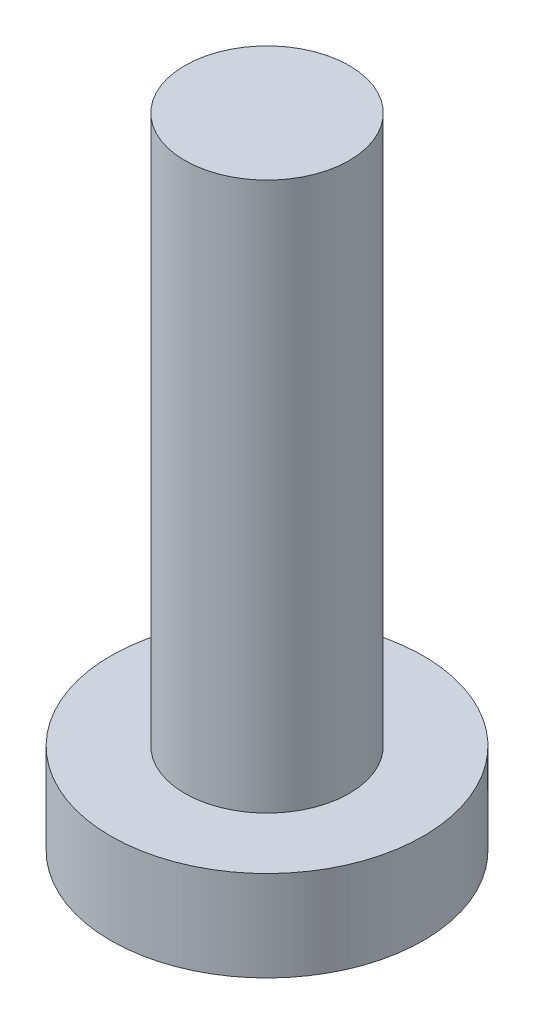
SolidWorks part; units mm, degrees
ref_plane "前视基准面" through (0, 0, 0) normal (0, 0, 1) x (1, 0, 0)
ref_plane "上视基准面" through (0, 0, 0) normal (0, 1, 0) x (1, 0, 0)
ref_plane "右视基准面" through (0, 0, 0) normal (1, 0, 0) x (0, 0, -1)
sketch "草图1" plane through (0, 0, 0) normal (0, 1, 0) x (1, 0, 0)
  circle A0 centre (0, 0) radius 2.85
  dimension "D1" = 5.7
extrude "凸台-拉伸1" add sketch "草图1" along normal blind 1.65
sketch "草图2" plane through (0, 1.65, 0) normal (0, 1, 0) x (1, 0, 0)
  circle A0 centre (0, 0) radius 1.5
  dimension "D1" = 3
extrude "凸台-拉伸2" add sketch "草图2" along normal blind 10
